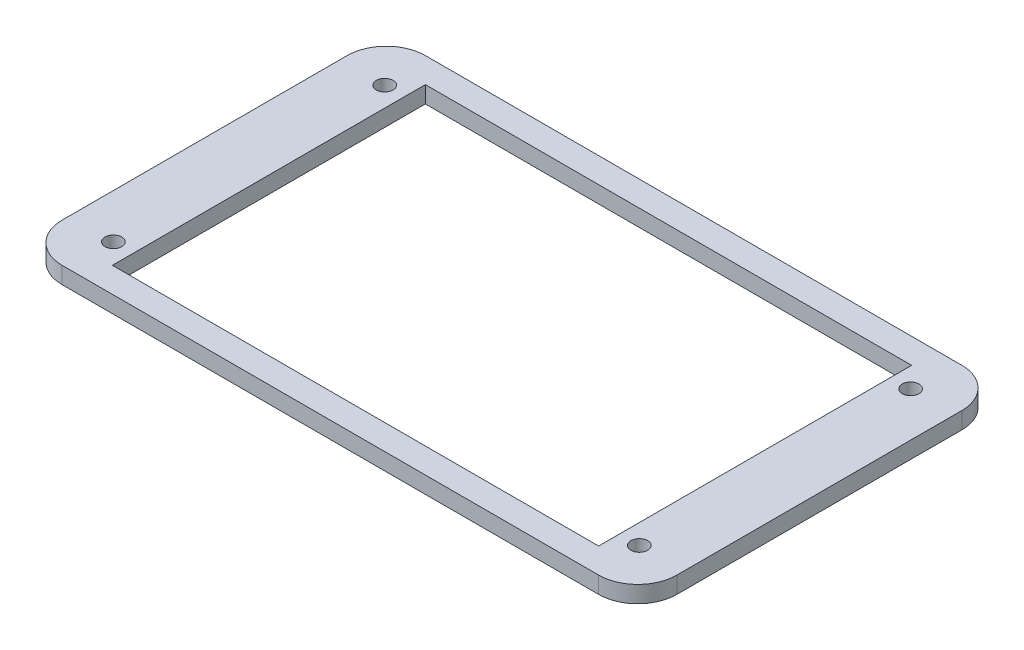
SolidWorks part; units mm, degrees
ref_plane "Front Plane" through (0, 0, 0) normal (0, 0, 1) x (1, 0, 0)
ref_plane "Top Plane" through (0, 0, 0) normal (0, 1, 0) x (1, 0, 0)
ref_plane "Right Plane" through (0, 0, 0) normal (1, 0, 0) x (0, 0, -1)
sketch "Sketch1" plane through (0, 0, 0) normal (0, 1, 0) x (1, 0, 0)
  line L1 (48, -32.5) -> (-48, -32.5)
  line L2 (55, -25.5) -> (55, 25.5)
  line L3 (48, 32.5) -> (-48, 32.5)
  line L4 (-55, -25.5) -> (-55, 25.5)
  line L5 (55, -32.5) -> (-55, 32.5) construction
  line L6 (55, 32.5) -> (-55, -32.5) construction
  line L7 (47.05, -24.27) -> (-47.05, -24.27) construction
  line L8 (47.05, -24.27) -> (47.05, 24.27) construction
  line L9 (47.05, 24.27) -> (-47.05, 24.27) construction
  line L10 (-47.05, -24.27) -> (-47.05, 24.27) construction
  line L11 (47.05, -24.27) -> (-47.05, 24.27) construction
  line L12 (47.05, 24.27) -> (-47.05, -24.27) construction
  circle A0 centre (-47.05, 24.27) radius 1.5
  circle A1 centre (-47.05, -24.27) radius 1.5
  circle A2 centre (47.05, -24.27) radius 1.5
  circle A3 centre (47.05, 24.27) radius 1.5
  arc A4 (-48, -32.5) -> (-55, -25.5) centre (-48, -25.5) cw
  arc A5 (48, -32.5) -> (55, -25.5) centre (48, -25.5) ccw
  arc A6 (55, 25.5) -> (48, 32.5) centre (48, 25.5) ccw
  arc A7 (-48, 32.5) -> (-55, 25.5) centre (-48, 25.5) ccw
  point P0 (0, 0)
  point P6 (0, 0)
  dimension "D5" = 7
  dimension "D1" = 110
  dimension "D2" = 65
  dimension "D3" = 94.1
  dimension "D4" = 48.54
extrude "Boss-Extrude1" add sketch "Sketch1" along normal mid plane 3
sketch "Sketch2" plane through (0, 1.5, 0) normal (0, 1, 0) x (1, 0, 0)
  line L1 (43.5, -28) -> (-43.5, -28)
  line L2 (43.5, -28) -> (43.5, 28)
  line L3 (43.5, 28) -> (-43.5, 28)
  line L4 (-43.5, -28) -> (-43.5, 28)
  line L5 (43.5, -28) -> (-43.5, 28) construction
  line L6 (43.5, 28) -> (-43.5, -28) construction
  point P0 (0, 0)
  dimension "D1" = 56
  dimension "D2" = 87
extrude "Cut-Extrude1" cut sketch "Sketch2" against normal up to next
